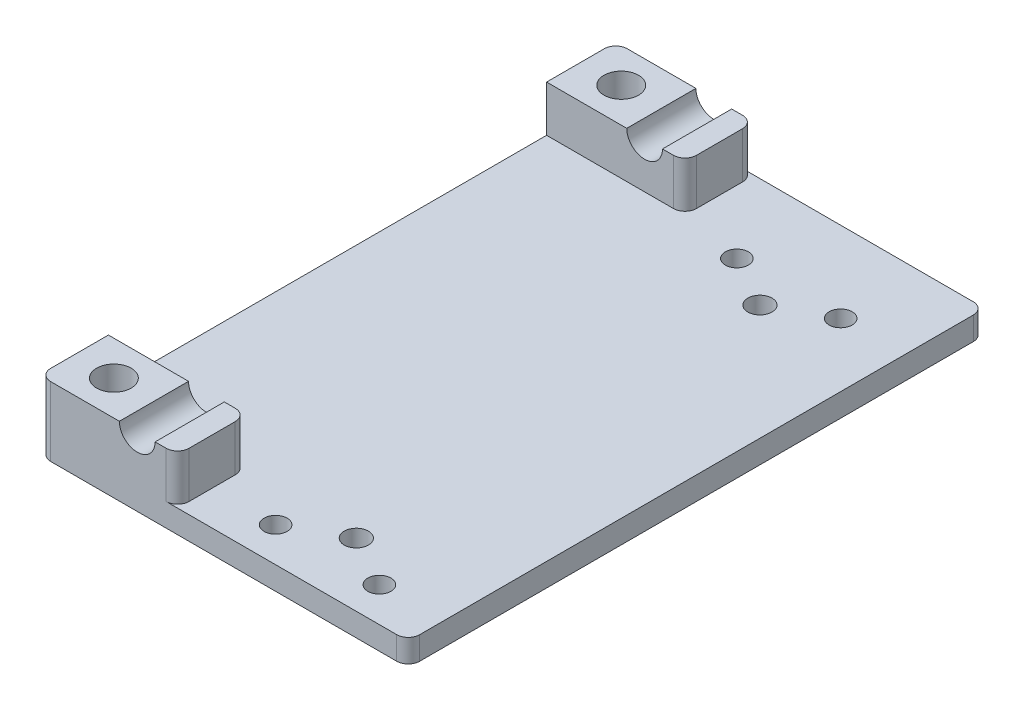
SolidWorks part; units mm, degrees
ref_plane "前基準面" through (0, 0, 0) normal (0, 0, 1) x (1, 0, 0)
ref_plane "上基準面" through (0, 0, 0) normal (0, 1, 0) x (1, 0, 0)
ref_plane "右基準面" through (0, 0, 0) normal (1, 0, 0) x (0, 0, -1)
sketch "草圖1" plane through (0, 0, 0) normal (0, 0, 1) x (1, 0, 0)
  line L0 (-12, 4) -> (0, 4) construction
  line L1 (0, 4) -> (0, 0)
  line L2 (0, 0) -> (20, 0)
  line L3 (20, 0) -> (20, -2)
  line L4 (20, -2) -> (-12, -2)
  line L5 (-12, -2) -> (-12, 4)
  line L6 (-12, 4) -> (-5.05, 4)
  line L7 (-1.95, 4) -> (0, 4)
  arc A0 (-5.05, 4) -> (-1.95, 4) centre (-3.5, 4) ccw
  dimension "D5" = 3.1
  dimension "D1" = 12
  dimension "D2" = 4
  dimension "D3" = 2
  dimension "D4" = 20
  dimension "D6" = 3.5
extrude "填料-伸長1" add sketch "草圖1" against normal blind 50
sketch "草圖2" plane through (0, 4, 0) normal (0, 1, 0) x (1, 0, 0)
  line L0 (-8.525, 50) -> (-8.525, 0) construction
  line L1 (-5.05, 50) -> (-12, 50) construction
  line L2 (-5.05, 0) -> (-12, 0) construction
  line L3 (10, 50) -> (10, 0) construction
  line L4 (20, 50) -> (0, 50) construction
  line L5 (20, 0) -> (0, 0) construction
  line L6 (14.5, 50) -> (14.5, 0) construction
  line L8 (5.5, 50) -> (5.5, 0) construction
  circle A0 centre (-8.525, 47) radius 1.5
  circle A1 centre (-8.525, 3) radius 1.5
  circle A2 centre (5.5, 43) radius 1
  circle A3 centre (14.5, 43) radius 1
  circle A4 centre (5.5, 3) radius 1
  circle A5 centre (14.5, 3) radius 1
  circle A6 centre (10, 5.5) radius 1.05
  circle A7 centre (10, 40.5) radius 1.05
  dimension "D1" = 3
  dimension "D2" = 3
  dimension "D7" = 2
  dimension "D8" = 2
  dimension "D9" = 2.1
  dimension "D10" = 2.1
  dimension "D11" = 2
  dimension "D12" = 2
  dimension "D3" = 3
  dimension "D4" = 3
  dimension "D5" = 4.5
  dimension "D6" = 4.5
  dimension "D13" = 35
  dimension "D14" = 40
  dimension "D15" = 2.5
  dimension "D16" = 7
extrude "除料-伸長1" cut sketch "草圖2" against normal through all
sketch "草圖3" plane through (0, 0, 0) normal (1, 0, 0) x (0, 0, -1)
  line L0 (50, 0) -> (0, 0) construction
  line L1 (6, 0) -> (44, 0)
  line L2 (6, 0) -> (6, 8.2129)
  line L3 (6, 8.2129) -> (44, 8.2129)
  line L4 (44, 0) -> (44, 8.2129)
  line L5 (0, 0) -> (0, 4) construction
  line L6 (50, 0) -> (50, 4) construction
  point P8 (50, 2)
  dimension "D1" = 6
  dimension "D2" = 6
extrude "除料-伸長2" cut sketch "草圖3" against normal blind 50
fillet "圓角1" radius 1 8 edges at (0, 2, -50) (0, 2, 0) (20, -1, -50) (20, -1, 0) (-12, 1, -50) (-12, 1, 0) (0, 2, -44) (0, 2, -6)
